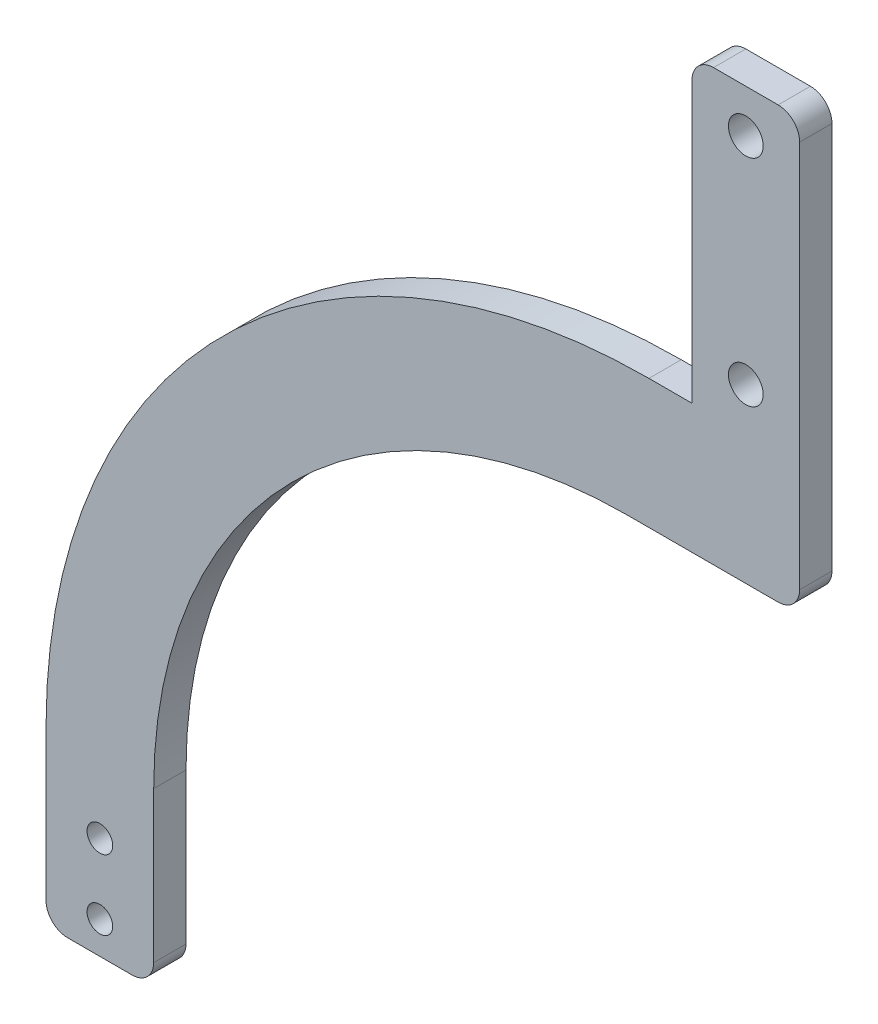
SolidWorks part; units mm, degrees
ref_plane "Front Plane" through (0, 0, 0) normal (0, 0, 1) x (1, 0, 0)
ref_plane "Top Plane" through (0, 0, 0) normal (0, 1, 0) x (1, 0, 0)
ref_plane "Right Plane" through (0, 0, 0) normal (1, 0, 0) x (0, 0, -1)
sketch "Sketch1" plane through (0, 0, 0) normal (0, 0, 1) x (1, 0, 0)
  line L0 (0, 1.625) -> (0, -1.625) construction
  line L1 (-2.5, -3.125) -> (-2.5, 3.875)
  line L2 (2.5, -3.125) -> (-2.5, -3.125)
  line L3 (2.5, -3.125) -> (2.5, 46.875) construction
  line L4 (2.5, 46.875) -> (-2.5, 46.875) construction
  line L5 (-2.5, -3.125) -> (-2.5, 46.875) construction
  line L6 (27.5, 46.875) -> (32.5, 46.875)
  line L7 (27.5, 46.875) -> (27.5, 32.875)
  line L8 (27.5, 32.875) -> (32.5, 32.875) construction
  line L9 (32.5, 46.875) -> (32.5, 32.875)
  line L10 (2.5, -3.125) -> (2.5, 3.875)
  line L11 (-2.5, 3.875) -> (-2.5, 32.875)
  line L12 (-2.5, 32.875) -> (27.5, 32.875)
  line L13 (32.5, 32.875) -> (32.5, 26.875)
  line L14 (32.5, 26.875) -> (2.5, 26.875)
  line L15 (2.5, 26.875) -> (2.5, 3.875)
  circle A0 centre (0, 1.625) radius 0.5956
  circle A1 centre (0, -1.625) radius 0.5956
  circle A2 centre (30, 44.875) radius 0.8065
  circle A3 centre (30, 34.875) radius 0.8065
  point P10 (0, -3.125)
  point P14 (30, 32.875)
  dimension "D2" = 1.1913
  dimension "D7" = 1.6129
  dimension "D1" = 3.25
  dimension "D3" = 5
  dimension "D4" = 1.5
  dimension "D5" = 50
  dimension "D6" = 10
  dimension "D8" = 2
  dimension "D9" = 30
  dimension "D10" = 5
  dimension "D11" = 2
  dimension "D12" = 7
  dimension "D13" = 6
extrude "Boss-Extrude1" add sketch "Sketch1" along normal blind 1.5
fillet "Fillet2" radius 22 1 edges at (2.5, 26.875, 0.75)
fillet "Fillet3" radius 28 1 edges at (-2.5, 32.875, 0.75)
fillet "Fillet1" radius 1 5 edges at (32.5, 46.875, 0.75) (27.5, 46.875, 0.75) (2.5, -3.125, 0.75) (-2.5, -3.125, 0.75) (32.5, 26.875, 0.75)
